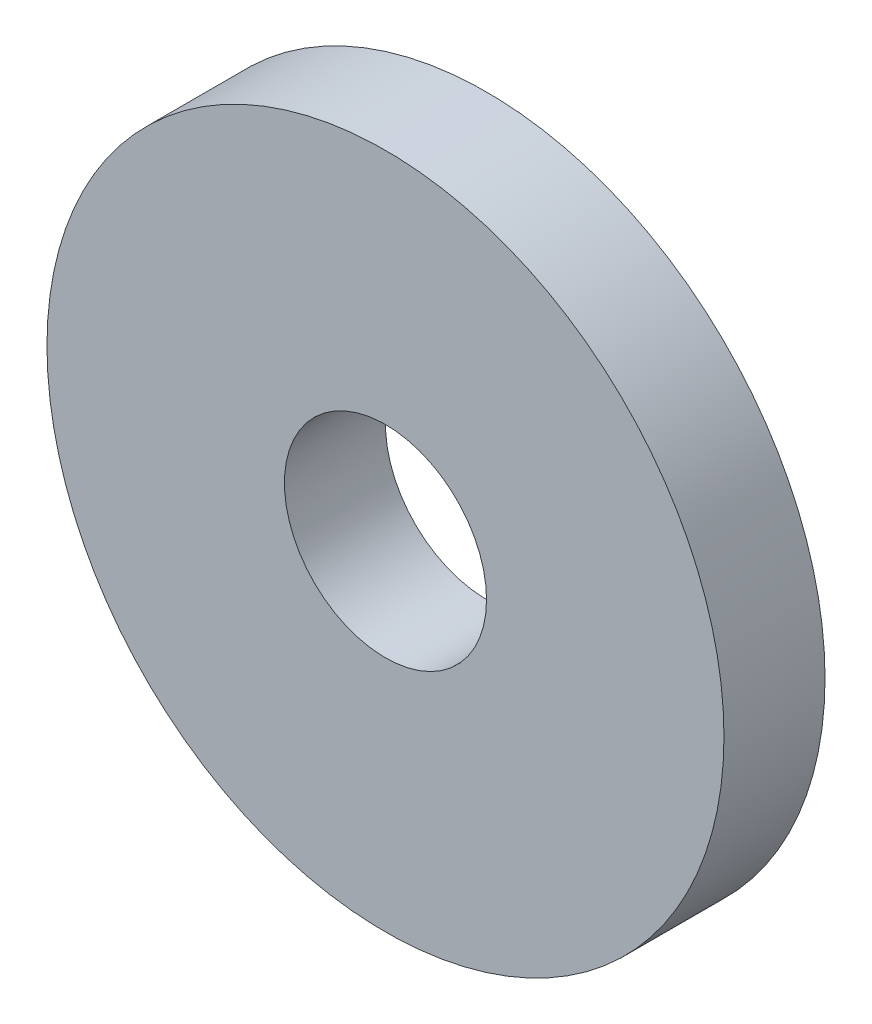
SolidWorks part; units mm, degrees
ref_plane "Front Plane" through (0, 0, 0) normal (0, 0, 1) x (1, 0, 0)
ref_plane "Top Plane" through (0, 0, 0) normal (0, 1, 0) x (1, 0, 0)
ref_plane "Right Plane" through (0, 0, 0) normal (1, 0, 0) x (0, 0, -1)
sketch "Sketch1" plane through (0, 0, 0) normal (0, 0, 1) x (1, 0, 0)
  circle A0 centre (0.5774, 0.0962) radius 3
  circle A1 centre (0.5774, 0.0962) radius 10.0499
extrude "Boss-Extrude1" add sketch "Sketch1" along normal blind 3
